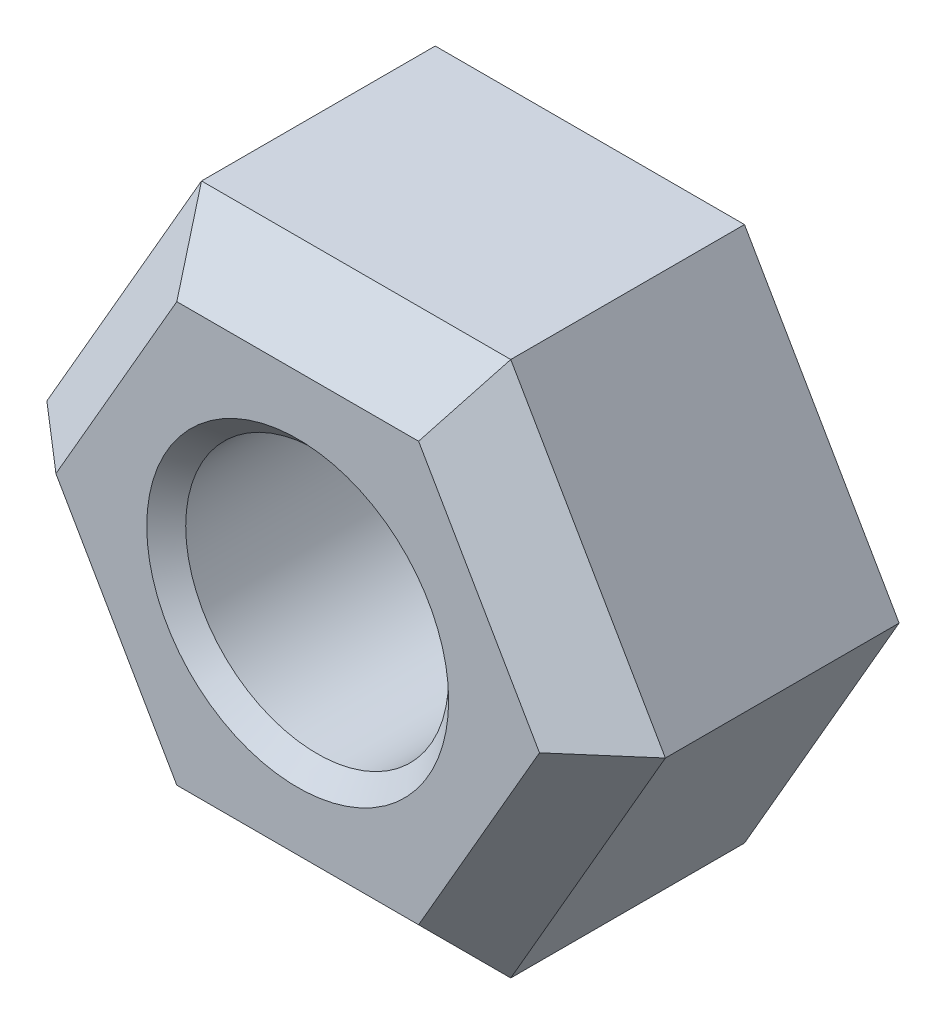
SolidWorks part; units mm, degrees
material "ABS"
ref_plane "正面" through (0, 0, 0) normal (0, 0, 1) x (1, 0, 0)
ref_plane "平面" through (0, 0, 0) normal (0, 1, 0) x (1, 0, 0)
ref_plane "右側面" through (0, 0, 0) normal (1, 0, 0) x (0, 0, -1)
sketch "ｽｹｯﾁ1" plane through (0, 0, 0) normal (0, 0, 1) x (1, 0, 0)
  line L1 (3.1754, 0) -> (1.5877, 2.75)
  line L2 (1.5877, 2.75) -> (-1.5877, 2.75)
  line L3 (-1.5877, 2.75) -> (-3.1754, 0)
  line L4 (-3.1754, 0) -> (-1.5877, -2.75)
  line L5 (-1.5877, -2.75) -> (1.5877, -2.75)
  line L6 (1.5877, -2.75) -> (3.1754, 0)
  circle A0 centre (0, 0) radius 2.75 construction
  circle A1 centre (0, 0) radius 1.35
  point P10 (0, 0)
  dimension "D1" = 2.7
  dimension "D2" = 5.5
extrude "ﾎﾞｽ - 押し出し1" add sketch "ｽｹｯﾁ1" along normal blind 3
chamfer "面取り1" distance 0.6 angle 45 6 edges at (-2.3816, -1.375, 3) (0, -2.75, 3) (-2.3816, 1.375, 3) (0, 2.75, 3) (2.3816, 1.375, 3) (2.3816, -1.375, 3)
chamfer "面取り2" distance 0.2 angle 45 2 edges at (1.35, 0, 0) (1.35, 0, 3)
